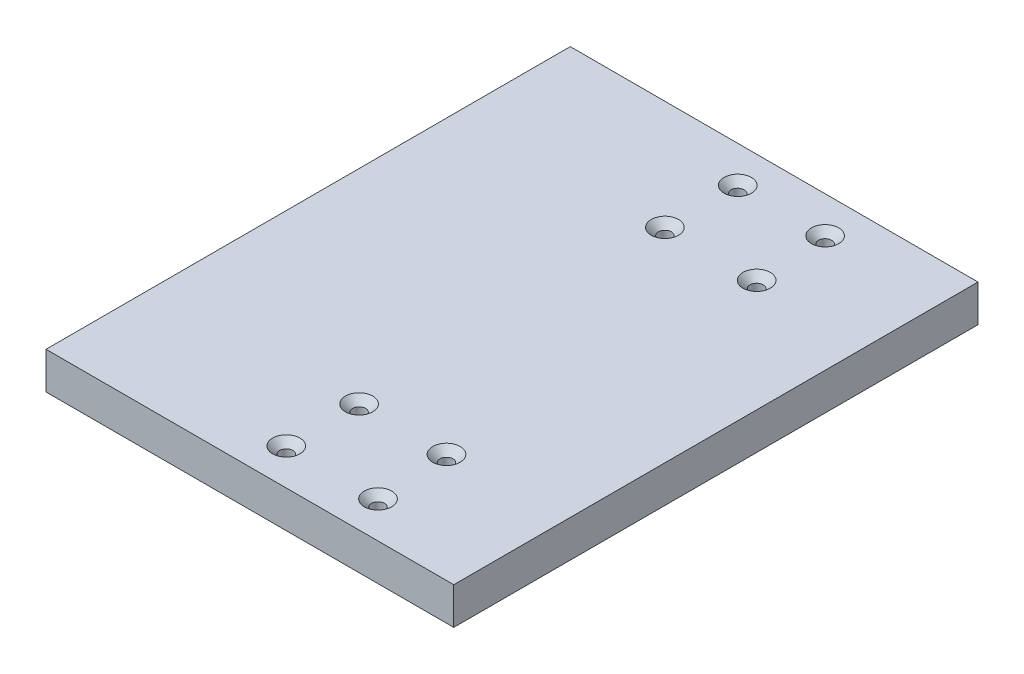
SolidWorks part; units mm, degrees
ref_plane "Front Plane" through (0, 0, 0) normal (0, 0, 1) x (1, 0, 0)
ref_plane "Top Plane" through (0, 0, 0) normal (0, 1, 0) x (1, 0, 0)
ref_plane "Right Plane" through (0, 0, 0) normal (1, 0, 0) x (0, 0, -1)
sketch "Sketch1" plane through (0, 0, 0) normal (0, 1, 0) x (1, 0, 0)
  line L1 (70, 90) -> (-70, 90)
  line L2 (70, 90) -> (70, -90)
  line L3 (70, -90) -> (-70, -90)
  line L4 (-70, 90) -> (-70, -90)
  line L5 (70, 90) -> (-70, -90) construction
  line L6 (70, -90) -> (-70, 90) construction
  point P0 (0, 0)
  dimension "D1" = 180
  dimension "D2" = 140
extrude "Boss-Extrude1" add sketch "Sketch1" along normal blind 12.7
sketch "Sketch2" plane through (0, 12.7, 0) normal (0, 1, 0) x (1, 0, 0)
  line L0 (-70, -90) -> (70, -90) construction
  line L1 (70, -90) -> (70, 90) construction
  point P0 (0, -52.5)
  point P1 (30, -52.5)
  point P2 (31.4877, -77.5)
  point P3 (0, -77.5)
  point P8 (0, 77.5)
  point P9 (30, 77.5)
  point P10 (31.4877, 52.5)
  point P11 (0, 52.5)
  dimension "D1" = 30
  dimension "D2" = 25
  dimension "D3" = 12.5
  dimension "D5" = 40
  dimension "D4" = 2
hole_wizard "CSK for M4 Flat Head Machine Screw1" positions "Sketch2" profile "Sketch3" countersink size "M4" standard "ANSI Metric" end condition through all
sketch "Sketch3" plane through (0, 12.7, 52.5) normal (1, 0, 0) x (0, 0, 1)
  line L0 (0, 0) -> (0, 12.7)
  line L1 (0, 12.7) -> (2.25, 12.7)
  line L2 (2.25, 12.7) -> (2.25, 2.45)
  line L3 (2.25, 2.45) -> (4.7, 0)
  line L5 (4.7, 0) -> (0, 0)
  line L6 (-2.25, 2.45) -> (-4.7, 0) construction
  line L11 (0, -6.35) -> (0, 107.95) construction
  dimension "Thru Hole Dia." = 4.5
  dimension "Thru Hole Depth" = 12.7
  dimension "Near C'Sink Dia." = 9.4
  dimension "Near C'Sink Angle" = 90
